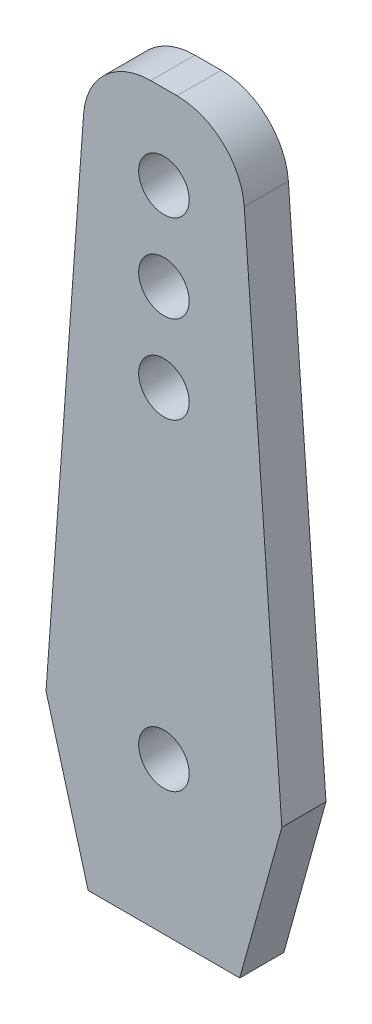
SolidWorks part; units mm, degrees
ref_plane "Front Plane" through (0, 0, 0) normal (0, 0, 1) x (1, 0, 0)
ref_plane "Top Plane" through (0, 0, 0) normal (0, 1, 0) x (1, 0, 0)
ref_plane "Right Plane" through (0, 0, 0) normal (1, 0, 0) x (0, 0, -1)
sketch "Sketch2" plane through (0, 0, 0) normal (0, 0, 1) x (1, 0, 0)
  line L0 (0, 0) -> (0, 38.7071) construction
  line L1 (-0.7794, 34.5) -> (0.7794, 34.5)
  line L2 (-4.5, -9) -> (4.5, -9)
  line L4 (-7, 0) -> (-4.5, -9)
  line L5 (7, 0) -> (4.5, -9)
  line L6 (-4.7689, 30.7891) -> (-7, 0)
  line L7 (4.7689, 30.7891) -> (7, 0)
  circle A0 centre (0, 0) radius 1.5
  circle A1 centre (0, 19.1) radius 1.5
  circle A2 centre (0, 24.3) radius 1.5
  circle A3 centre (0, 29.5) radius 1.5
  arc A4 (4.7689, 30.7891) -> (0.7794, 34.5) centre (0.7794, 30.5) ccw
  arc A5 (-4.7689, 30.7891) -> (-0.7794, 34.5) centre (-0.7794, 30.5) cw
  point P13 (0, 34.5)
  point P16 (0, -9)
  point P19 (0, 0)
  point P28 (4.5, 34.5)
  point P31 (-4.5, 34.5)
  dimension "D4" = 3
  dimension "D5" = 9
  dimension "D9" = 4
  dimension "D1" = 19.1
  dimension "D2" = 5.2
  dimension "D3" = 5.2
  dimension "D6" = 14
  dimension "D7" = 9
  dimension "D8" = 43.5
extrude "Boss-Extrude1" add sketch "Sketch2" along normal blind 2.62
